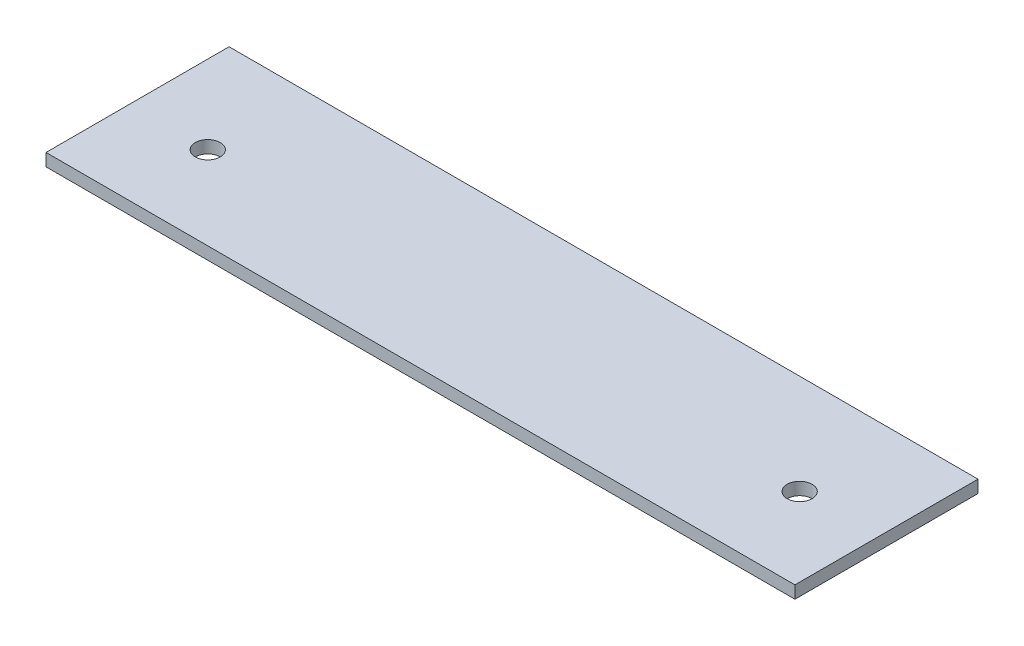
SolidWorks part; units mm, degrees
material "1060 Alloy"
ref_plane "Front Plane" through (0, 0, 0) normal (0, 0, 1) x (1, 0, 0)
ref_plane "Top Plane" through (0, 0, 0) normal (0, 1, 0) x (1, 0, 0)
ref_plane "Right Plane" through (0, 0, 0) normal (1, 0, 0) x (0, 0, -1)
sketch "Sketch1" plane through (0, 0, 0) normal (0, 1, 0) x (1, 0, 0)
  line L1 (-45, -11) -> (45, -11)
  line L2 (-45, -11) -> (-45, 11)
  line L3 (-45, 11) -> (45, 11)
  line L4 (45, -11) -> (45, 11)
  line L5 (-45, -11) -> (45, 11) construction
  line L6 (-45, 11) -> (45, -11) construction
  line L7 (0, 11) -> (0, -11) construction
  circle A0 centre (35.565, -1) radius 1.5
  circle A1 centre (-35.565, -1) radius 1.5
  point P0 (0, 0)
  point P12 (0, 0)
  dimension "D3" = 3
  dimension "D1" = 90
  dimension "D2" = 22
  dimension "D4" = 71.13
  dimension "D5" = 10
extrude "Boss-Extrude1" add sketch "Sketch1" against normal blind 1.5
